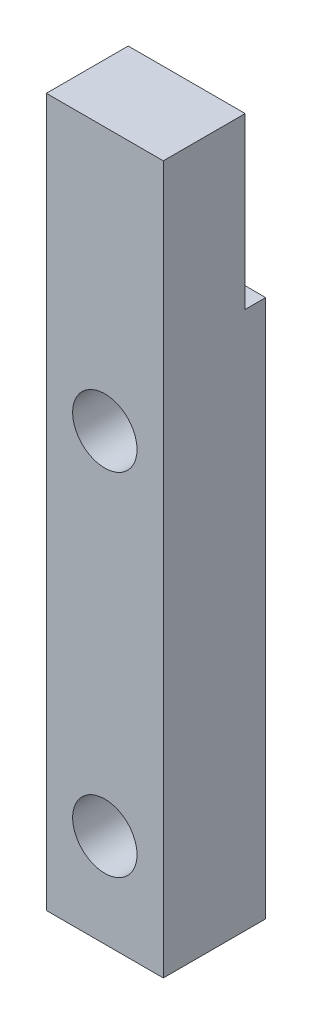
SolidWorks part; units mm, degrees
ref_plane "Front Plane" through (0, 0, 0) normal (0, 0, 1) x (1, 0, 0)
ref_plane "Top Plane" through (0, 0, 0) normal (0, 1, 0) x (1, 0, 0)
ref_plane "Right Plane" through (0, 0, 0) normal (1, 0, 0) x (0, 0, -1)
sketch "Sketch1" plane through (0, 0, 300) normal (0, 0, 1) x (1, 0, 0)
  line L0 (-135.2935, 66) -> (164.7065, 66) construction
  line L1 (75, 66) -> (95, 66)
  line L5 (75, 10) -> (75, 50)
  line L8 (75, 60) -> (75, 50)
  line L10 (85, -26) -> (75, -26)
  line L11 (75, -26) -> (75, 10)
  line L15 (85, -26) -> (95, -26)
  line L16 (75, 60) -> (75, 66)
  line L18 (95, -26) -> (95, 66)
  circle A0 centre (85, -10) radius 5.5
  circle A5 centre (85, 50) radius 5.5
  circle A6 centre (85, 50) radius 5.5
  dimension "D1" = 2.5
extrude "Boss-Extrude1" add sketch "Sketch1" along normal blind 3.5
sketch "Sketch2" plane through (0, 0, 303.5) normal (0, 0, 1) x (1, 0, 0)
  line L0 (75, 10) -> (75, 85)
  line L6 (75, 85) -> (75, 95)
  line L7 (75, 95) -> (95, 95)
  line L9 (75, 10) -> (75, -26)
  line L10 (75, -26) -> (95, -26)
  line L11 (95, -26) -> (95, 66) construction
  line L12 (75, -26) -> (95, -26) construction
  line L13 (95, -26) -> (95, 66)
  line L14 (95, 66) -> (95, 95)
  circle A3 centre (85, 50) radius 5.5 construction
  circle A7 centre (85, 50) radius 5.5
  circle A9 centre (85, -10) radius 5.5
  circle A10 centre (85, -10) radius 5.5
  point P3 (0, 0)
  dimension "D1" = 0
extrude "Boss-Extrude2" add sketch "Sketch2" along normal blind 14
